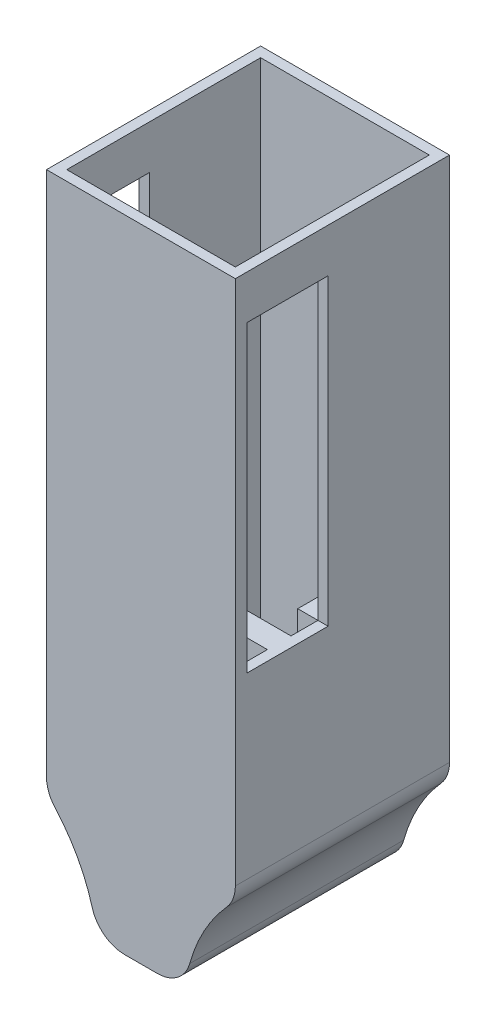
SolidWorks part; units mm, degrees
material "Aleación 1060"
ref_plane "Alzado" through (0, 0, 0) normal (0, 0, 1) x (1, 0, 0)
ref_plane "Planta" through (0, 0, 0) normal (0, 1, 0) x (1, 0, 0)
ref_plane "Vista lateral" through (0, 0, 0) normal (1, 0, 0) x (0, 0, -1)
sketch "Croquis2" plane through (0, 0, 0) normal (0, 0, 1) x (1, 0, 0)
  line L1 (-28, -95) -> (28, -95)
  line L2 (-28, -95) -> (-28, 95)
  line L3 (-28, 95) -> (28, 95)
  line L4 (28, -95) -> (28, 95)
  line L5 (-28, -95) -> (28, 95) construction
  line L6 (-28, 95) -> (28, -95) construction
  point P0 (0, 0)
  dimension "D1" = 56
  dimension "D2" = 190
extrude "Saliente-Extruir1" add sketch "Croquis2" along normal blind 63.5
sketch "Croquis20" plane through (0, 0, 63.5) normal (0, 0, 1) x (1, 0, 0)
  line L1 (-28, -95) -> (28, -95) construction
  line L2 (28, -95) -> (28, 95) construction
  line L4 (-28, 95) -> (-28, -95) construction
  line L5 (-33.5344, -65) -> (34.8448, -65) construction
  line L6 (-13, -95) -> (-28, -95)
  line L7 (-28, -95) -> (-28, -65)
  line L8 (13, -95) -> (28, -95)
  line L9 (28, -95) -> (28, -65)
  arc A0 (-13, -95) -> (-28, -65) centre (-62.6307, -101.0654) ccw
  arc A1 (13, -95) -> (28, -65) centre (62.6307, -101.0654) cw
  dimension "D3" = 50
  dimension "D4" = 50
  dimension "D1" = 15
  dimension "D2" = 15
  dimension "D5" = 30
extrude "Cortar-Extruir6" cut sketch "Croquis20" against normal blind 65
fillet "Redondeo1" radius 10 4 edges at (28, -65, 31.75) (13, -95, 31.75) (-13, -95, 31.75) (-28, -65, 31.75)
shell "Vaciado2" thickness 3
sketch "Croquis9" plane through (0, 0, 60.5) normal (0, 0, -1) x (-1, 0, 0)
  line L1 (-28, 95) -> (28, 95) construction
  line L2 (28, 95) -> (28, -60.9643) construction
  circle A0 centre (0, 70) radius 4
  dimension "D1" = 8
  dimension "D2" = 25
  dimension "D3" = 28
sketch "Croquis10" plane through (28, 0, 0) normal (1, 0, 0) x (0, 0, -1)
  line L0 (-63.5, 95) -> (0, 95) construction
  line L1 (-60, 82) -> (-36, 82)
  line L2 (-60, 82) -> (-60, -8)
  line L3 (-60, -8) -> (-36, -8)
  line L4 (-36, 82) -> (-36, -8)
  line L6 (0, -60.9643) -> (0, 95) construction
  dimension "D1" = 13
  dimension "D2" = 36
  dimension "D3" = 24
  dimension "D4" = 90
extrude "Cortar-Extruir1" cut sketch "Croquis10" against normal blind 129
sketch "Croquis12" plane through (0, -92, 0) normal (0, 1, 0) x (1, 0, 0)
  line L1 (25, -51) -> (-25, -51)
  line L2 (25, -51) -> (25, -44)
  line L3 (25, -44) -> (-25, -44)
  line L4 (-25, -51) -> (-25, -44)
  dimension "D1" = 9.5
  dimension "D2" = 7
extrude "Saliente-Extruir2" add sketch "Croquis12" along normal blind 84
sketch "Croquis13" plane through (0, -8, 0) normal (0, 1, 0) x (1, 0, 0)
  line L0 (25, -44) -> (-25, -44) construction
  line L1 (-4, -51.0316) -> (4, -51.0316)
  line L2 (-4, -51.0316) -> (-4, -44)
  line L3 (-4, -44) -> (4, -44)
  line L4 (4, -51.0316) -> (4, -44)
  line L5 (-4, -51.0316) -> (4, -44) construction
  line L6 (-4, -44) -> (4, -51.0316) construction
  line L7 (28, -63.5) -> (28, 0) construction
  point P0 (0, -47.5158)
  dimension "D2" = 0
  dimension "D3" = 8
  dimension "D4" = 28
extrude "Cortar-Extruir2" cut sketch "Croquis13" against normal blind 84
sketch "Croquis14" plane through (0, -95, 0) normal (0, -1, 0) x (1, 0, 0)
  circle A0 centre (0, 28) radius 5
  dimension "D1" = 10
extrude "Cortar-Extruir3" cut sketch "Croquis14" against normal blind 84
sketch "Croquis15" plane through (0, 0, 0) normal (0, 0, -1) x (-1, 0, 0)
  line L0 (-28, 95) -> (28, 95) construction
  line L1 (-25, -65) -> (25, -65)
  line L2 (-25, -65) -> (-25, 25)
  line L3 (-25, 25) -> (25, 25)
  line L4 (25, -65) -> (25, 25)
  line L5 (4.8215, -95) -> (-4.8215, -95) construction
  line L6 (28, 95) -> (28, -60.9643) construction
  line L7 (-28, -60.9643) -> (-28, 95) construction
  dimension "D1" = 70
  dimension "D2" = 30
  dimension "D3" = 3
  dimension "D4" = 3
extrude "Cortar-Extruir4" [suppressed] cut sketch "Croquis15" against normal blind 3
sketch "Croquis17" plane through (0, 0, 44) normal (0, 0, -1) x (-1, 0, 0)
  line L4 (11.963, -92) -> (25, -92)
  line L5 (25, -92) -> (25, -68.1423)
  line L6 (-25, -68.1423) -> (-25, -92)
  line L7 (-25, -92) -> (-11.963, -92)
  arc A0 (14.4564, -87.6776) -> (25, -68.1423) centre (62.6307, -101.0654) cw
  arc A1 (-14.4564, -87.6776) -> (-25, -68.1423) centre (-62.6307, -101.0654) ccw
  arc A2 (-11.963, -92) -> (-14.4564, -87.6776) centre (-4.8215, -85) cw
  arc A3 (14.4564, -87.6776) -> (11.963, -92) centre (4.8215, -85) cw
extrude "Cortar-Extruir5" cut sketch "Croquis17" against normal blind 10
sketch "Croquis18" plane through (-25, 0, 0) normal (1, 0, 0) x (0, 0, -1)
  line L1 (-21, -65) -> (-36, -65)
  line L2 (-21, -65) -> (-21, -8)
  line L3 (-21, -8) -> (-36, -8)
  line L4 (-36, -65) -> (-36, -8)
  dimension "D1" = 15
extrude "Saliente-Extruir4" add sketch "Croquis18" along normal blind 6 separate body
sketch "Croquis19" plane through (25, 0, 0) normal (-1, 0, 0) x (0, 0, 1)
  line L1 (21, -65) -> (36, -65)
  line L2 (21, -65) -> (21, -8)
  line L3 (21, -8) -> (36, -8)
  line L4 (36, -65) -> (36, -8)
  dimension "D1" = 15
extrude "Saliente-Extruir5" add sketch "Croquis19" along normal blind 6 separate body
sketch "Croquis22" plane through (0, -95, 0) normal (0, -1, 0) x (1, 0, 0)
  line L1 (-6.7785, 50.5) -> (6.8215, 50.5)
  line L2 (-6.7785, 50.5) -> (-6.7785, 44.3)
  line L3 (-6.7785, 44.3) -> (6.8215, 44.3)
  line L4 (6.8215, 50.5) -> (6.8215, 44.3)
  line L6 (4.8215, 0) -> (4.8215, 26.6761) construction
  circle A0 centre (0, 28) radius 5
  dimension "D1" = 13.6
  dimension "D2" = 6.2
  dimension "D3" = 22.5
  dimension "D4" = 2
extrude "Cortar-Extruir7" cut sketch "Croquis22" against normal blind 20
sketch "Croquis23" plane through (0, -75, 0) normal (0, -1, 0) x (1, 0, 0)
  line L1 (-6.7785, 51) -> (6.8215, 51)
  line L2 (-6.7785, 51) -> (-6.7785, 44)
  line L3 (-6.7785, 44) -> (6.8215, 44)
  line L4 (6.8215, 51) -> (6.8215, 44)
  line L6 (-4.8215, 60.5) -> (4.8215, 60.5) construction
  dimension "D1" = 7
  dimension "D2" = 9.5
extrude "Cortar-Extruir8" cut sketch "Croquis23" against normal blind 10
